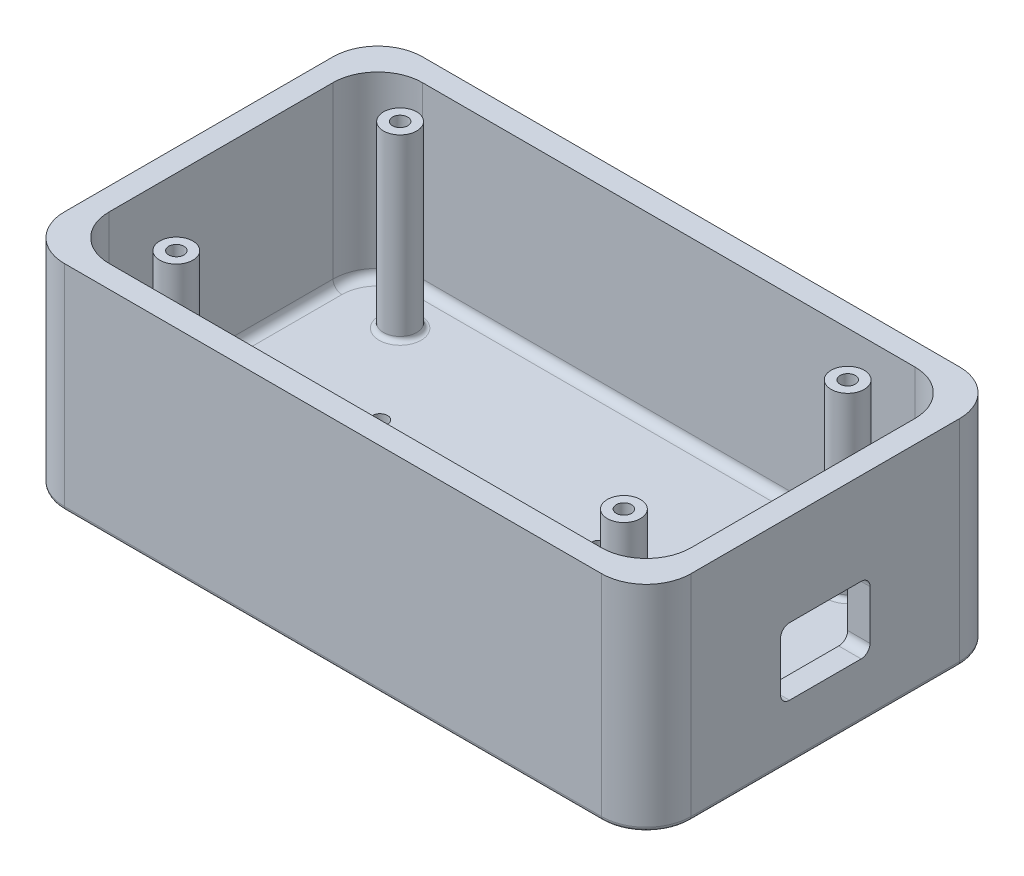
SolidWorks part; units mm, degrees
ref_plane "Front Plane" through (0, 0, 0) normal (0, 0, 1) x (1, 0, 0)
ref_plane "Top Plane" through (0, 0, 0) normal (0, 1, 0) x (1, 0, 0)
ref_plane "Right Plane" through (0, 0, 0) normal (1, 0, 0) x (0, 0, -1)
sketch "Sketch2" plane through (0, 0, 0) normal (0, 1, 0) x (1, 0, 0)
  line L1 (-60, -40) -> (60, -40)
  line L2 (-70, -30) -> (-70, 30)
  line L3 (-60, 40) -> (60, 40)
  line L4 (70, -30) -> (70, 30)
  line L5 (-70, -40) -> (70, 40) construction
  line L6 (-70, 40) -> (70, -40) construction
  arc A0 (70, -30) -> (60, -40) centre (60, -30) cw
  arc A1 (-60, -40) -> (-70, -30) centre (-60, -30) cw
  arc A2 (-70, 30) -> (-60, 40) centre (-60, 30) cw
  arc A3 (60, 40) -> (70, 30) centre (60, 30) cw
  point P0 (0, 0)
  dimension "D3" = 10
  dimension "D1" = 140
  dimension "D2" = 80
extrude "Boss-Extrude1" add sketch "Sketch2" along normal blind 48
sketch "Sketch3" plane through (0, 48, 0) normal (0, 1, 0) x (1, 0, 0)
  line L1 (-55, -35) -> (55, -35)
  line L2 (-65, -25) -> (-65, 25)
  line L3 (-55, 35) -> (55, 35)
  line L4 (65, -25) -> (65, 25)
  line L5 (-65, -35) -> (65, 35) construction
  line L6 (-65, 35) -> (65, -35) construction
  arc A0 (55, 35) -> (65, 25) centre (55, 25) cw
  arc A1 (65, -25) -> (55, -35) centre (55, -25) cw
  arc A2 (-55, -35) -> (-65, -25) centre (-55, -25) cw
  arc A3 (-65, 25) -> (-55, 35) centre (-55, 25) cw
  point P0 (0, 0)
  dimension "D3" = 10
  dimension "D1" = 70
  dimension "D2" = 130
extrude "Cut-Extrude1" cut sketch "Sketch3" against normal blind 40
sketch "Sketch4" plane through (0, 8, 0) normal (0, 1, 0) x (1, 0, 0)
  line L1 (-50, -25) -> (50, -25) construction
  line L2 (-50, -25) -> (-50, 25) construction
  line L3 (-50, 25) -> (50, 25) construction
  line L4 (50, -25) -> (50, 25) construction
  line L5 (-50, -25) -> (50, 25) construction
  line L6 (-50, 25) -> (50, -25) construction
  circle A0 centre (-50, 25) radius 1.7
  circle A1 centre (50, 25) radius 1.7
  circle A2 centre (50, -25) radius 1.7
  circle A3 centre (-50, -25) radius 1.7
  point P0 (0, 0)
  dimension "D1" = 50
  dimension "D2" = 100
extrude "Cut-Extrude2" cut sketch "Sketch4" against normal through all
sketch "Sketch5" plane through (0, 0, 0) normal (0, -1, 0) x (-1, 0, 0)
  line L1 (53, -25) -> (51.5, -22.4019)
  line L2 (51.5, -22.4019) -> (48.5, -22.4019)
  line L3 (48.5, -22.4019) -> (47, -25)
  line L4 (47, -25) -> (48.5, -27.5981)
  line L5 (48.5, -27.5981) -> (51.5, -27.5981)
  line L6 (51.5, -27.5981) -> (53, -25)
  line L7 (47, 25) -> (48.5, 22.4019)
  line L8 (48.5, 22.4019) -> (51.5, 22.4019)
  line L9 (51.5, 22.4019) -> (53, 25)
  line L10 (53, 25) -> (51.5, 27.5981)
  line L11 (51.5, 27.5981) -> (48.5, 27.5981)
  line L12 (48.5, 27.5981) -> (47, 25)
  line L13 (-53, 25) -> (-51.5, 22.4019)
  line L14 (-51.5, 22.4019) -> (-48.5, 22.4019)
  line L15 (-48.5, 22.4019) -> (-47, 25)
  line L16 (-47, 25) -> (-48.5, 27.5981)
  line L17 (-48.5, 27.5981) -> (-51.5, 27.5981)
  line L18 (-51.5, 27.5981) -> (-53, 25)
  line L19 (-53, -25) -> (-51.5, -27.5981)
  line L20 (-51.5, -27.5981) -> (-48.5, -27.5981)
  line L21 (-48.5, -27.5981) -> (-47, -25)
  line L22 (-47, -25) -> (-48.5, -22.4019)
  line L23 (-48.5, -22.4019) -> (-51.5, -22.4019)
  line L24 (-51.5, -22.4019) -> (-53, -25)
  circle A0 centre (50, -25) radius 2.5981 construction
  circle A1 centre (50, 25) radius 2.5981 construction
  circle A2 centre (-50, 25) radius 2.5981 construction
  circle A3 centre (-50, -25) radius 2.5981 construction
  dimension "D1" = 3
  dimension "D2" = 3
  dimension "D3" = 3
  dimension "D4" = 3
extrude "Cut-Extrude3" cut sketch "Sketch5" against normal blind 2.7
sketch "Sketch6" plane through (0, 8, 0) normal (0, 1, 0) x (1, 0, 0)
  circle A0 centre (-50, 25) radius 3.7
  circle A1 centre (-50, -25) radius 3.7
  circle A2 centre (50, 25) radius 3.7
  circle A3 centre (50, -25) radius 3.7
extrude "Boss-Extrude2" add sketch "Sketch6" along normal blind 40
sketch "Sketch7" plane through (0, 48, 0) normal (0, 1, 0) x (1, 0, 0)
  circle A0 centre (-50, 25) radius 1.7
  circle A1 centre (50, 25) radius 1.7
  circle A2 centre (-50, -25) radius 1.7
  circle A3 centre (50, -25) radius 1.7
extrude "Cut-Extrude4" cut sketch "Sketch7" against normal through all
fillet "Fillet1" radius 1 8 edges at (-67.0711, 0, 37.0711) (-70, 0, 0) (-67.0711, 0, -37.0711) (0, 0, -40) (67.0711, 0, -37.0711) (70, 0, 0) (67.0711, 0, 37.0711) (0, 0, 40)
fillet "Fillet3" radius 2 8 edges at (62.0711, 8, -32.0711) (65, 8, 0) (62.0711, 8, 32.0711) (0, 8, 35) (-62.0711, 8, 32.0711) (-65, 8, 0) (-62.0711, 8, -32.0711) (0, 8, -35)
fillet "Fillet4" radius 1 4 edges at (50, 8, 21.3) (-50, 8, 21.3) (-50, 8, -28.7) (50, 8, -28.7)
sketch "Sketch8" plane through (0, 8, 0) normal (0, 1, 0) x (1, 0, 0)
  circle A0 centre (-34.5, 5) radius 1.7
  circle A1 centre (-34.5, -5) radius 1.7
  circle A2 centre (14.5, 5) radius 1.7
  circle A3 centre (14.5, -5) radius 1.7
extrude "Cut-Extrude5" cut sketch "Sketch8" against normal through all
sketch "Sketch9" plane through (0, 0, 0) normal (0, -1, 0) x (-1, 0, 0)
  line L1 (-17.5, -5) -> (-16, -7.5981)
  line L2 (-16, -7.5981) -> (-13, -7.5981)
  line L3 (-13, -7.5981) -> (-11.5, -5)
  line L4 (-11.5, -5) -> (-13, -2.4019)
  line L5 (-13, -2.4019) -> (-16, -2.4019)
  line L6 (-16, -2.4019) -> (-17.5, -5)
  line L7 (-17.5, 5) -> (-16, 2.4019)
  line L8 (-16, 2.4019) -> (-13, 2.4019)
  line L9 (-13, 2.4019) -> (-11.5, 5)
  line L10 (-11.5, 5) -> (-13, 7.5981)
  line L11 (-13, 7.5981) -> (-16, 7.5981)
  line L12 (-16, 7.5981) -> (-17.5, 5)
  line L13 (31.5, 5) -> (33, 2.4019)
  line L14 (33, 2.4019) -> (36, 2.4019)
  line L15 (36, 2.4019) -> (37.5, 5)
  line L16 (37.5, 5) -> (36, 7.5981)
  line L17 (36, 7.5981) -> (33, 7.5981)
  line L18 (33, 7.5981) -> (31.5, 5)
  line L19 (31.5, -5) -> (33, -7.5981)
  line L20 (33, -7.5981) -> (36, -7.5981)
  line L21 (36, -7.5981) -> (37.5, -5)
  line L22 (37.5, -5) -> (36, -2.4019)
  line L23 (36, -2.4019) -> (33, -2.4019)
  line L24 (33, -2.4019) -> (31.5, -5)
  circle A0 centre (-14.5, -5) radius 2.5981 construction
  circle A1 centre (-14.5, 5) radius 2.5981 construction
  circle A2 centre (34.5, 5) radius 2.5981 construction
  circle A3 centre (34.5, -5) radius 2.5981 construction
  dimension "D1" = 3
  dimension "D2" = 3
  dimension "D3" = 3
  dimension "D4" = 3
extrude "Cut-Extrude6" cut sketch "Sketch9" against normal blind 2.7
sketch "Sketch10" plane through (-70, 0, 0) normal (-1, 0, 0) x (0, 0, 1)
  line L1 (-8, 12.5) -> (8, 12.5)
  line L2 (-10, 14.5) -> (-10, 25.5)
  line L3 (-8, 27.5) -> (8, 27.5)
  line L4 (10, 14.5) -> (10, 25.5)
  line L5 (-10, 12.5) -> (10, 27.5) construction
  line L6 (-10, 27.5) -> (10, 12.5) construction
  arc A0 (10, 14.5) -> (8, 12.5) centre (8, 14.5) cw
  arc A1 (-8, 12.5) -> (-10, 14.5) centre (-8, 14.5) cw
  arc A2 (-10, 25.5) -> (-8, 27.5) centre (-8, 25.5) cw
  arc A3 (8, 27.5) -> (10, 25.5) centre (8, 25.5) cw
  point P0 (0, 20)
  point P17 (0, 0)
  dimension "D3" = 2
  dimension "D1" = 20
  dimension "D2" = 15
extrude "Cut-Extrude7" cut sketch "Sketch10" against normal blind 20 from offset 130
